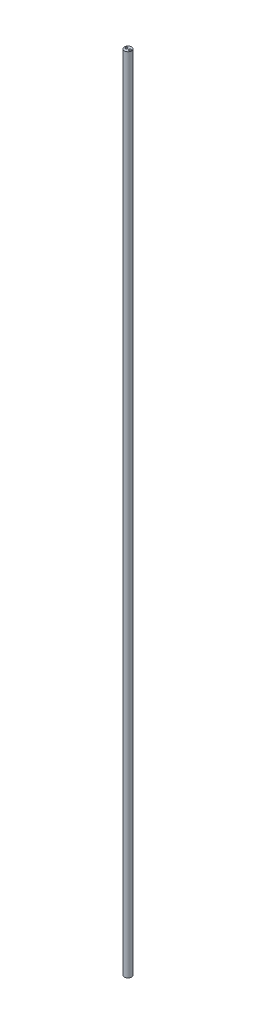
SolidWorks part; units mm, degrees
ref_plane "Front Plane" through (0, 0, 0) normal (0, 0, 1) x (1, 0, 0)
ref_plane "Top Plane" through (0, 0, 0) normal (0, 1, 0) x (1, 0, 0)
ref_plane "Right Plane" through (0, 0, 0) normal (1, 0, 0) x (0, 0, -1)
sketch "CROSS SECTION" plane through (0, 0, 0) normal (0, 1, 0) x (1, 0, 0)
  line L0 (-0.088, 0) -> (0.088, 0) construction
  circle A0 centre (0, 0) radius 0.088
  circle A1 centre (-0.0367, 0) radius 0.0288
  circle A2 centre (0.0469, 0) radius 0.029
  ellipse E0 centre (-0.0029, 0) end of major axis (-0.0029, -0.0037) minor radius 0.0027
  point P10 (0.0179, 0)
  point P16 (-0.0079, 0)
  point P17 (0.0759, 0)
  point P18 (-0.0655, 0)
  dimension "D1" = 0.176
  dimension "D2" = 0.0576
  dimension "D3" = 0.058
  dimension "D4" = 0.0053
  dimension "D5" = 0.0073
  dimension "D6" = 0.0023
  dimension "D7" = 0.0181
  dimension "D8" = 0.0225
extrude "Body Extrude" add sketch "CROSS SECTION" along normal blind 20 contours L0 A0 A2 E0 A1 | A0 L0 A1 E0 A2 | L0 E0 | E0 L0
